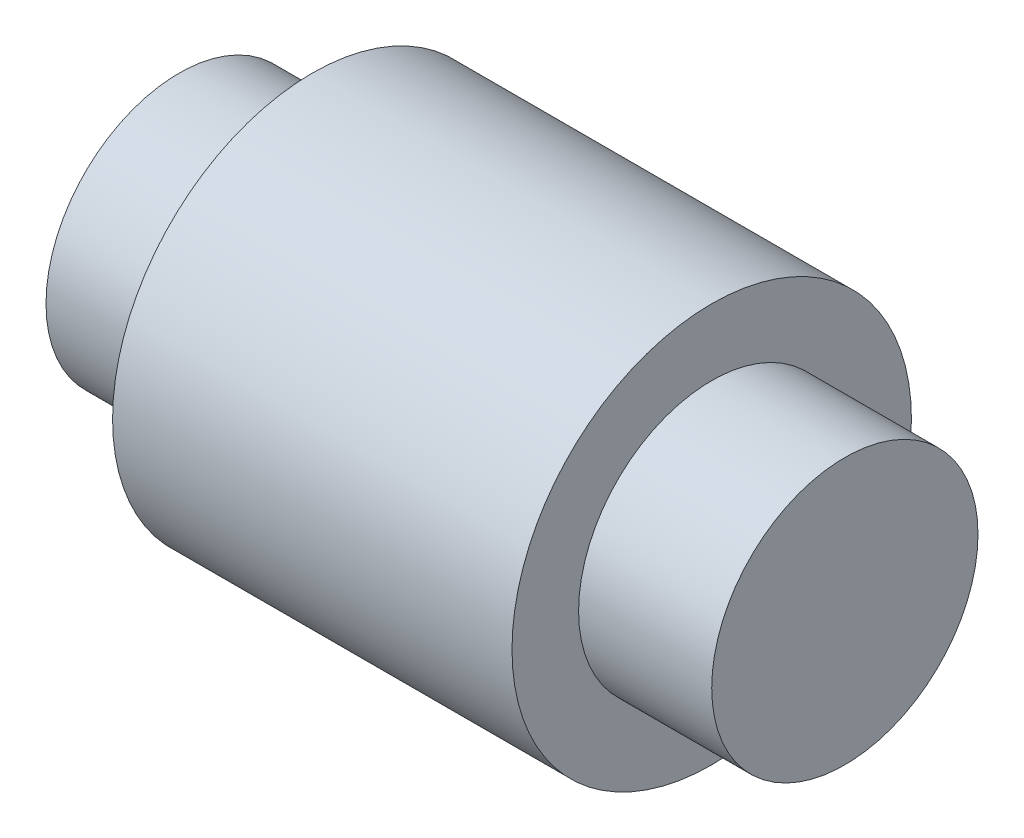
SolidWorks part; units mm, degrees
ref_plane "Спереди" through (0, 0, 0) normal (0, 0, 1) x (1, 0, 0)
ref_plane "Сверху" through (0, 0, 0) normal (0, 1, 0) x (1, 0, 0)
ref_plane "Справа" through (0, 0, 0) normal (1, 0, 0) x (0, 0, -1)
sketch "Эскиз1" plane through (0, 0, 0) normal (0, 0, 1) x (1, 0, 0)
  line L0 (0, 0) -> (100, 0)
  line L1 (0, 0) -> (0, 20)
  line L2 (0, 20) -> (20, 20)
  line L3 (20, 20) -> (20, 30)
  line L4 (20, 30) -> (80, 30)
  line L5 (80, 30) -> (80, 20)
  line L6 (80, 20) -> (100, 20)
  line L7 (100, 0) -> (100, 20)
revolve "Повернуть1" add sketch "Эскиз1" angle 360 about L0
